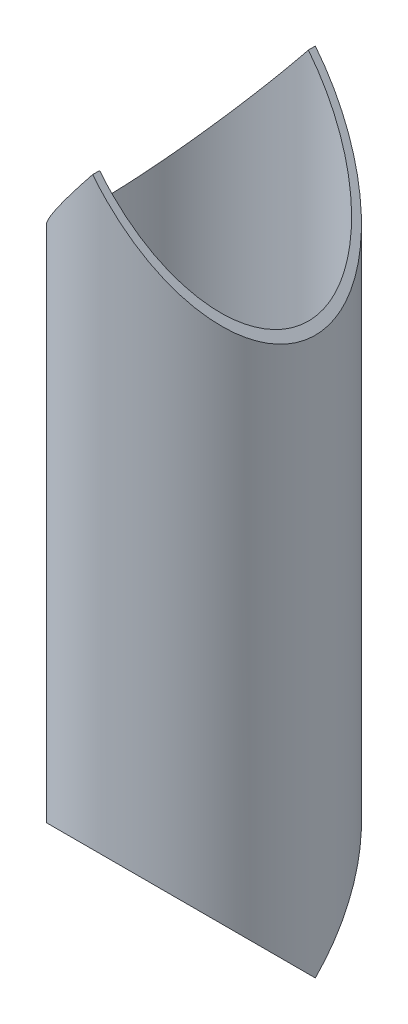
SolidWorks part; units mm, degrees
material "Acrylic (Medium-high impact)"
ref_plane "Front Plane" through (0, 0, 0) normal (0, 0, 1) x (1, 0, 0)
ref_plane "Top Plane" through (0, 0, 0) normal (0, 1, 0) x (1, 0, 0)
ref_plane "Right Plane" through (0, 0, 0) normal (1, 0, 0) x (0, 0, -1)
sketch "Sketch1" plane through (0, 0, 0) normal (0, 1, 0) x (1, 0, 0)
  circle A0 centre (0, 0) radius 25.4
  circle A1 centre (0, 0) radius 23.8125
  dimension "D1" = 50.8
  dimension "D2" = 1.5875
extrude "Boss-Extrude1" add sketch "Sketch1" along normal blind 158.75
sketch "Sketch2" plane through (0, 0, 0) normal (0, 0, 1) x (1, 0, 0)
  line L2 (-25.4, 158.75) -> (-25.4, 0) construction
  line L3 (25.4, 0) -> (25.4, 158.75) construction
  line L4 (25.4, 127) -> (25.4, 158.75)
  line L5 (25.4, 158.75) -> (-0.9601, 166.5405)
  line L6 (-0.9601, 166.5405) -> (-25.4, 158.75)
  line L7 (-25.4, 158.75) -> (-25.4, 127)
  line L9 (-25.4, 127) -> (0, 158.75)
  line L10 (0, 158.75) -> (25.4, 127)
  line L11 (25.4, 158.75) -> (-25.4, 158.75) construction
extrude "Cut-Extrude1" cut sketch "Sketch2" against normal through all and the other way through all
sketch "Sketch3" plane through (0, 0, 0) normal (1, 0, 0) x (0, 0, -1)
  line L0 (-25.4, 158.75) -> (-25.4, 0) construction
  line L1 (25.4, 0) -> (25.4, 158.75) construction
  line L2 (-25.4, 25.4) -> (-25.4, 0)
  line L3 (-25.4, 0) -> (0.0326, -12.1128)
  line L4 (0.0326, -12.1128) -> (25.4, 0)
  line L5 (25.4, 0) -> (25.4, 25.4)
  line L7 (25.4, 25.4) -> (0, 0)
  line L8 (-23.8125, 0) -> (23.8125, 0) construction
  line L9 (0, 0) -> (-25.4, 25.4)
extrude "Cut-Extrude2" cut sketch "Sketch3" against normal through all and the other way through all
